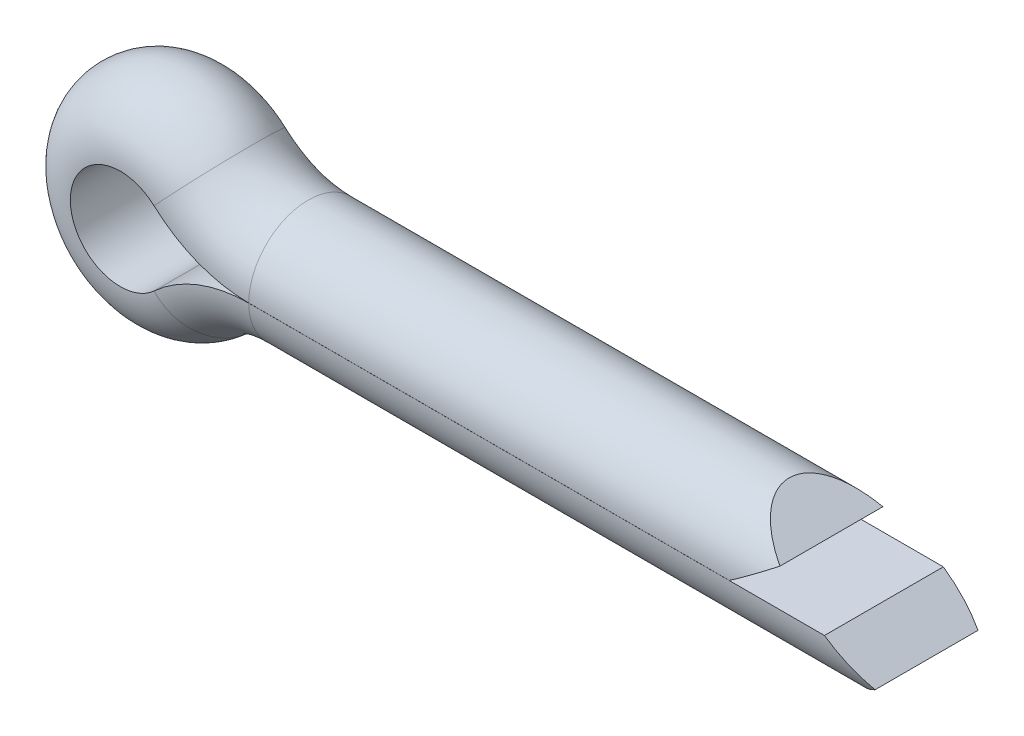
SolidWorks part; units mm, degrees
ref_plane "Front" through (0, 0, 0) normal (0, 0, 1) x (1, 0, 0)
ref_plane "Top" through (0, 0, 0) normal (0, 1, 0) x (1, 0, 0)
ref_plane "Right" through (0, 0, 0) normal (1, 0, 0) x (0, 0, -1)
sketch "草图2" plane through (0, 0, 0) normal (0, 0, 1) x (1, 0, 0)
  line L0 (22, 2.5) -> (0, 2.5)
  line L1 (0, -2.5) -> (26, -2.5)
  line L2 (0, 0) -> (49.7718, 0) construction
  line L3 (0, 0) -> (0, 16.5256) construction
  line L4 (-10, 0) -> (-10, 14.2137) construction
  arc A0 (0, 2.5) -> (-2.2922, 3.3914) centre (0, 5.8929) cw
  arc A1 (-2.2922, 3.3914) -> (-2.2922, -3.3914) centre (-5.4, 0) ccw
  arc A2 (-2.2922, -3.3914) -> (0, -2.5) centre (0, -5.8929) cw
  dimension "Diameter" = 5
  dimension "c" = 9.2
  dimension "b" = 10
  dimension "l" = 22
  dimension "a" = 4
ref_plane "SectionPlane" through (22, 0, 0) normal (1, 0, 0) x (0, 0, -1)
sketch "草图1" plane through (22, 0, 0) normal (1, 0, 0) x (0, 0, -1)
  line L1 (-2.5, 0.002) -> (2.5, 0.002)
  arc A0 (2.5, 0.002) -> (-2.5, 0.002) centre (0, 0) ccw
  dimension "Diameter" = 5
  dimension "D1" = 0.002
sweep "Body" add profiles "草图1" path "草图2"
sketch "草图3" plane through (0, 0, 0) normal (0, 0, 1) x (1, 0, 0)
  line L0 (0, 0) -> (0, 16.2682) construction
  line L1 (0, 0) -> (75.9079, 0) construction
  line L2 (0, 0) -> (26, 0) construction
  line L3 (22, 1.251) -> (20.2105, 2.51)
  line L4 (22, 0.002) -> (22, 2.5) construction
  line L6 (22, 1.251) -> (20.2049, 0)
  line L7 (26, -1.251) -> (24.2049, 0)
  line L8 (26, -2.5) -> (26, -0.002) construction
  line L9 (26, -1.251) -> (24.2105, -2.51)
  line L10 (24.2049, 0) -> (20.2049, 0)
  line L11 (20.2105, 2.51) -> (26.01, 2.51)
  line L12 (26.01, 2.51) -> (26.01, -2.51)
  line L13 (26.01, -2.51) -> (24.2105, -2.51)
  line L14 (22, 2.5) -> (0, 2.5) construction
  dimension "D1" = 0.01
  dimension "D2" = 0.01
  dimension "D3" = 70
  dimension "D4" = 70
extrude "ConeCut" cut sketch "草图3" against normal through all and the other way through all
equation "' \"Diameter@草图2\" = 9.5"
equation "' \"c@草图2\" = 19"
equation "' \"b@草图2\" = 20"
equation "' \"a@草图2\" = 6.3"
equation "' \"l@草图2\" = 45"
equation "' \"Diameter@草图2\" = 1"
equation "' \"c@草图2\" = 2"
equation "' \"b@草图2\" = 3"
equation "' \"a@草图2\" = 2.5"
equation "' \"l@草图2\" = 8"
equation "' \"Diameter@草图2\" = 0.5"
equation "' \"c@草图2\" = 1"
equation "' \"b@草图2\" = 2"
equation "' \"a@草图2\" = 1.6"
equation "' \"l@草图2\" = 4"
equation "\"Diameter@草图1\" = \"Diameter@草图2\""
equation "\"Length@SectionPlane\" = \"l@草图2\""
